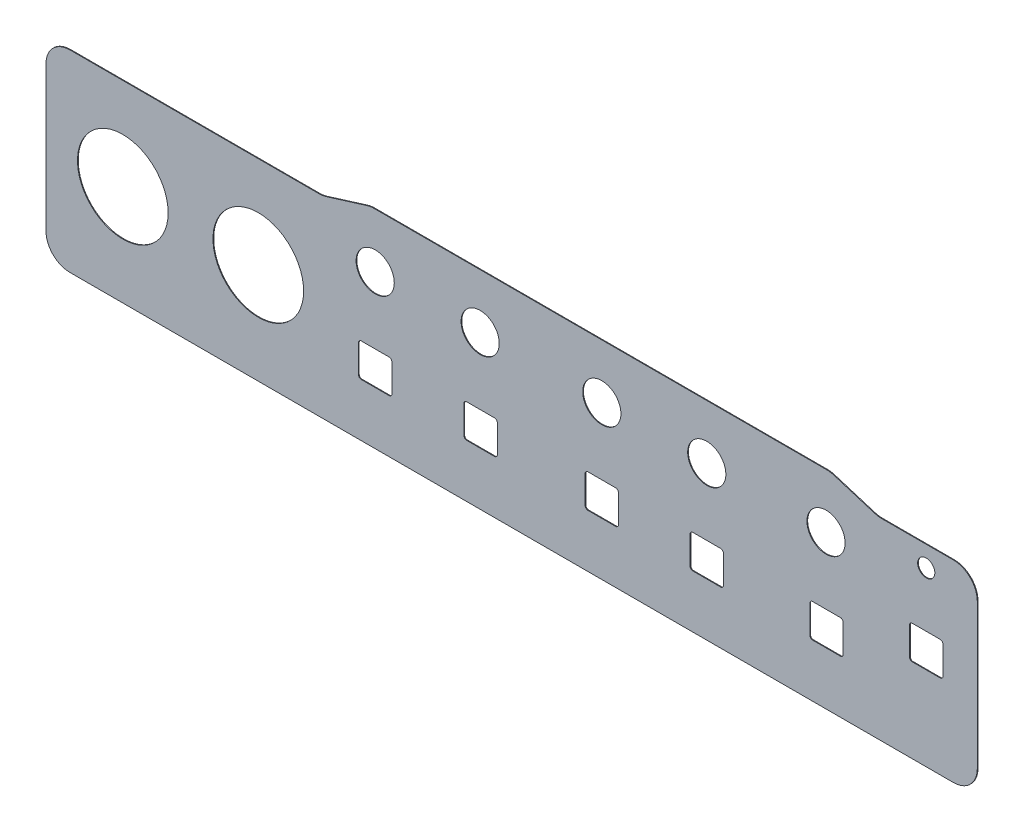
SolidWorks part; units mm, degrees
ref_plane "Спереди" through (0, 0, 0) normal (0, 0, 1) x (1, 0, 0)
ref_plane "Сверху" through (0, 0, 0) normal (0, 1, 0) x (1, 0, 0)
ref_plane "Справа" through (0, 0, 0) normal (1, 0, 0) x (0, 0, -1)
other "Configuration Table"
sketch "Printed_film_profile" plane through (0, 0, 0) normal (0, 0, 1) x (1, 0, 0)
  line L0 (2.4, -6.6) -> (187.6, -6.6)
  line L1 (192.6, -1.6) -> (192.6, 28.8)
  line L2 (187.6, 33.8) -> (172.5572, 33.8)
  line L3 (171.0767, 34.0242) -> (162.5233, 36.6758)
  line L4 (161.0428, 36.9) -> (66.1572, 36.9)
  line L5 (64.6767, 36.6758) -> (56.1233, 34.0242)
  line L6 (54.6428, 33.8) -> (2.4, 33.8)
  line L7 (-2.6, 28.8) -> (-2.6, -1.6)
  arc A0 (-2.6, -1.6) -> (2.4, -6.6) centre (2.4, -1.6) ccw
  arc A1 (187.6, -6.6) -> (192.6, -1.6) centre (187.6, -1.6) ccw
  arc A2 (192.6, 28.8) -> (187.6, 33.8) centre (187.6, 28.8) ccw
  arc A3 (172.5572, 33.8) -> (171.0767, 34.0242) centre (172.5572, 38.8) cw
  arc A4 (162.5233, 36.6758) -> (161.0428, 36.9) centre (161.0428, 31.9) ccw
  arc A5 (66.1572, 36.9) -> (64.6767, 36.6758) centre (66.1572, 31.9) ccw
  arc A6 (56.1233, 34.0242) -> (54.6428, 33.8) centre (54.6428, 38.8) cw
  arc A7 (2.4, 33.8) -> (-2.6, 28.8) centre (2.4, 28.8) ccw
extrude "Printed_film" add sketch "Printed_film_profile" along normal blind 0.15 from offset 14.65
sketch "Opening_BNC_Channel_0_profile" plane through (0, 0, 0) normal (0, 0, 1) x (1, 0, 0)
  circle A0 centre (13.5, 14.5) radius 9.5
extrude "Opening_BNC_Channel_0" cut sketch "Opening_BNC_Channel_0_profile" against normal blind 0.35 from offset 14.9
sketch "Opening_BNC_Channel_1_profile" plane through (0, 0, 0) normal (0, 0, 1) x (1, 0, 0)
  circle A0 centre (41.9, 14.5) radius 9.5
extrude "Opening_BNC_Channel_1" cut sketch "Opening_BNC_Channel_1_profile" against normal blind 0.35 from offset 14.9
sketch "Opening_LED_RUN_profile" plane through (0, 0, 0) normal (0, 0, 1) x (1, 0, 0)
  circle A0 centre (181.9, 29.5) radius 1.8
extrude "Opening_LED_RUN" cut sketch "Opening_LED_RUN_profile" against normal blind 0.35 from offset 14.9
sketch "Opening_FUNC_profile" plane through (0, 0, 0) normal (0, 0, 1) x (1, 0, 0)
  circle A0 centre (160.9, 25.5) radius 4
extrude "Opening_FUNC" cut sketch "Opening_FUNC_profile" against normal blind 0.35 from offset 14.9
sketch "Opening_TRG_MODE_profile" plane through (0, 0, 0) normal (0, 0, 1) x (1, 0, 0)
  line L0 (133, 4.5) -> (138.8, 4.5)
  line L1 (139.4, 5.1) -> (139.4, 10.9)
  line L2 (138.8, 11.5) -> (133, 11.5)
  line L3 (132.4, 10.9) -> (132.4, 5.1)
  arc A0 (138.8, 4.5) -> (139.4, 5.1) centre (138.8, 5.1) ccw
  arc A1 (139.4, 10.9) -> (138.8, 11.5) centre (138.8, 10.9) ccw
  arc A2 (133, 11.5) -> (132.4, 10.9) centre (133, 10.9) ccw
  arc A3 (132.4, 5.1) -> (133, 4.5) centre (133, 5.1) ccw
extrude "Opening_TRG_MODE" cut sketch "Opening_TRG_MODE_profile" against normal blind 0.35 from offset 14.9
sketch "Opening_CURSOR_profile" plane through (0, 0, 0) normal (0, 0, 1) x (1, 0, 0)
  line L0 (111, 4.5) -> (116.8, 4.5)
  line L1 (117.4, 5.1) -> (117.4, 10.9)
  line L2 (116.8, 11.5) -> (111, 11.5)
  line L3 (110.4, 10.9) -> (110.4, 5.1)
  arc A0 (116.8, 4.5) -> (117.4, 5.1) centre (116.8, 5.1) ccw
  arc A1 (117.4, 10.9) -> (116.8, 11.5) centre (116.8, 10.9) ccw
  arc A2 (111, 11.5) -> (110.4, 10.9) centre (111, 10.9) ccw
  arc A3 (110.4, 5.1) -> (111, 4.5) centre (111, 5.1) ccw
extrude "Opening_CURSOR" cut sketch "Opening_CURSOR_profile" against normal blind 0.35 from offset 14.9
sketch "Opening_EN_CH1_profile" plane through (0, 0, 0) normal (0, 0, 1) x (1, 0, 0)
  line L0 (85.6, 4.5) -> (91.4, 4.5)
  line L1 (92, 5.1) -> (92, 10.9)
  line L2 (91.4, 11.5) -> (85.6, 11.5)
  line L3 (85, 10.9) -> (85, 5.1)
  arc A0 (91.4, 4.5) -> (92, 5.1) centre (91.4, 5.1) ccw
  arc A1 (92, 10.9) -> (91.4, 11.5) centre (91.4, 10.9) ccw
  arc A2 (85.6, 11.5) -> (85, 10.9) centre (85.6, 10.9) ccw
  arc A3 (85, 5.1) -> (85.6, 4.5) centre (85.6, 5.1) ccw
extrude "Opening_EN_CH1" cut sketch "Opening_EN_CH1_profile" against normal blind 0.35 from offset 14.9
sketch "Opening_TRG_profile" plane through (0, 0, 0) normal (0, 0, 1) x (1, 0, 0)
  circle A0 centre (135.9, 25.5) radius 4
extrude "Opening_TRG" cut sketch "Opening_TRG_profile" against normal blind 0.35 from offset 14.9
sketch "Opening_TIME_profile" plane through (0, 0, 0) normal (0, 0, 1) x (1, 0, 0)
  circle A0 centre (113.9, 25.5) radius 4
extrude "Opening_TIME" cut sketch "Opening_TIME_profile" against normal blind 0.35 from offset 14.9
sketch "Opening_SET_CH1_profile" plane through (0, 0, 0) normal (0, 0, 1) x (1, 0, 0)
  circle A0 centre (88.4, 25.5) radius 4
extrude "Opening_SET_CH1" cut sketch "Opening_SET_CH1_profile" against normal blind 0.35 from offset 14.9
sketch "Opening_SET_CH0_profile" plane through (0, 0, 0) normal (0, 0, 1) x (1, 0, 0)
  circle A0 centre (66.4, 25.5) radius 4
extrude "Opening_SET_CH0" cut sketch "Opening_SET_CH0_profile" against normal blind 0.35 from offset 14.9
sketch "Opening_RUN_STOP_profile" plane through (0, 0, 0) normal (0, 0, 1) x (1, 0, 0)
  line L0 (179, 11) -> (184.8, 11)
  line L1 (185.4, 11.6) -> (185.4, 17.4)
  line L2 (184.8, 18) -> (179, 18)
  line L3 (178.4, 17.4) -> (178.4, 11.6)
  arc A0 (184.8, 11) -> (185.4, 11.6) centre (184.8, 11.6) ccw
  arc A1 (185.4, 17.4) -> (184.8, 18) centre (184.8, 17.4) ccw
  arc A2 (179, 18) -> (178.4, 17.4) centre (179, 17.4) ccw
  arc A3 (178.4, 11.6) -> (179, 11) centre (179, 11.6) ccw
extrude "Opening_RUN_STOP" cut sketch "Opening_RUN_STOP_profile" against normal blind 0.35 from offset 14.9
sketch "Opening_MENU_BACK_profile" plane through (0, 0, 0) normal (0, 0, 1) x (1, 0, 0)
  line L0 (158.1, 4.5) -> (163.9, 4.5)
  line L1 (164.5, 5.1) -> (164.5, 10.9)
  line L2 (163.9, 11.5) -> (158.1, 11.5)
  line L3 (157.5, 10.9) -> (157.5, 5.1)
  arc A0 (163.9, 4.5) -> (164.5, 5.1) centre (163.9, 5.1) ccw
  arc A1 (164.5, 10.9) -> (163.9, 11.5) centre (163.9, 10.9) ccw
  arc A2 (158.1, 11.5) -> (157.5, 10.9) centre (158.1, 10.9) ccw
  arc A3 (157.5, 5.1) -> (158.1, 4.5) centre (158.1, 5.1) ccw
extrude "Opening_MENU_BACK" cut sketch "Opening_MENU_BACK_profile" against normal blind 0.35 from offset 14.9
sketch "Opening_EN_CH0_profile" plane through (0, 0, 0) normal (0, 0, 1) x (1, 0, 0)
  line L0 (63.5, 4.5) -> (69.3, 4.5)
  line L1 (69.9, 5.1) -> (69.9, 10.9)
  line L2 (69.3, 11.5) -> (63.5, 11.5)
  line L3 (62.9, 10.9) -> (62.9, 5.1)
  arc A0 (69.3, 4.5) -> (69.9, 5.1) centre (69.3, 5.1) ccw
  arc A1 (69.9, 10.9) -> (69.3, 11.5) centre (69.3, 10.9) ccw
  arc A2 (63.5, 11.5) -> (62.9, 10.9) centre (63.5, 10.9) ccw
  arc A3 (62.9, 5.1) -> (63.5, 4.5) centre (63.5, 5.1) ccw
extrude "Opening_EN_CH0" cut sketch "Opening_EN_CH0_profile" against normal blind 0.35 from offset 14.9
